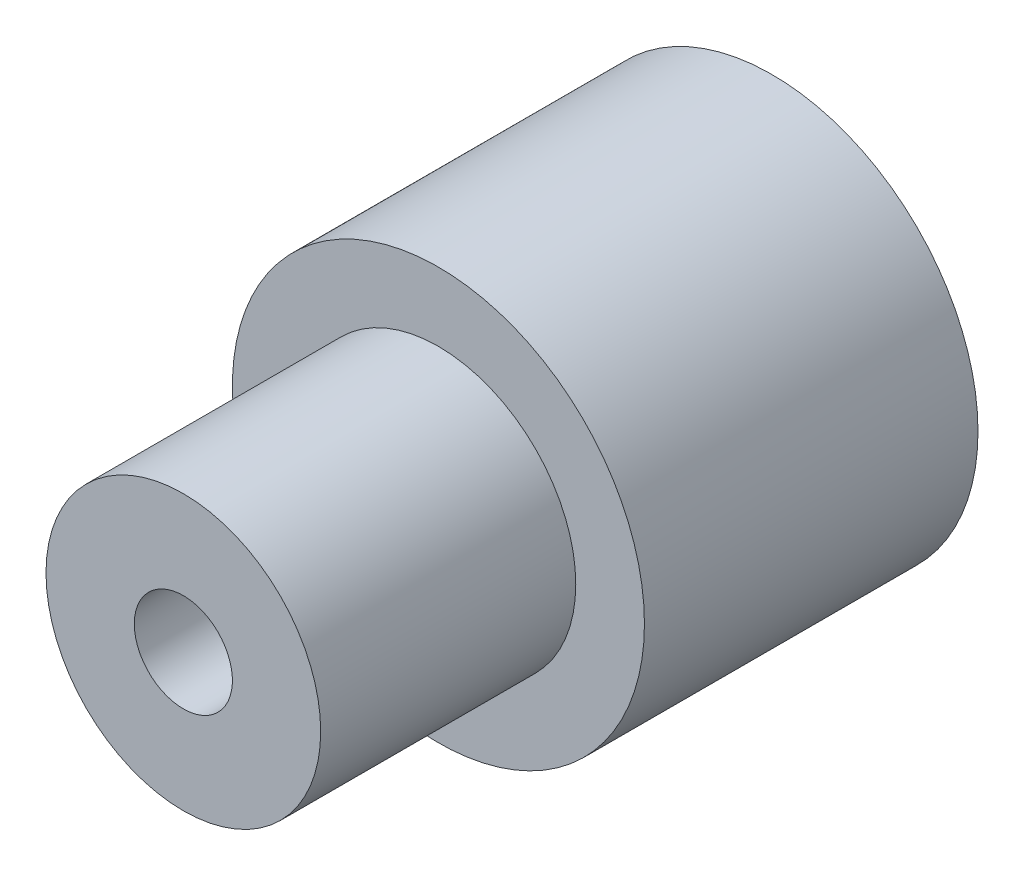
SolidWorks part; units mm, degrees
ref_plane "Alzado" through (0, 0, 0) normal (0, 0, 1) x (1, 0, 0)
ref_plane "Planta" through (0, 0, 0) normal (0, 1, 0) x (1, 0, 0)
ref_plane "Vista lateral" through (0, 0, 0) normal (1, 0, 0) x (0, 0, -1)
sketch "Croquis1" plane through (0, 0, 0) normal (0, 0, 1) x (1, 0, 0)
  circle A0 centre (0, 0) radius 10.5
  circle A1 centre (0, 0) radius 7
  dimension "D1" = 21
  dimension "D2" = 14
extrude "Saliente-Extruir1" add sketch "Croquis1" along normal blind 17 contours A1 | A0 A1
sketch "Croquis2" plane through (0, 0, 0) normal (0, 0, 1) x (1, 0, 0)
  circle A0 centre (0, 0) radius 7
  dimension "D1" = 14
extrude "Saliente-Extruir2" add sketch "Croquis2" along normal blind 30
sketch "Croquis3" plane through (0, 0, 0) normal (0, 0, 1) x (1, 0, 0)
  circle A0 centre (0, 0) radius 2.5
  dimension "D1" = 5
extrude "Cortar-Extruir1" cut sketch "Croquis3" along normal blind 58
